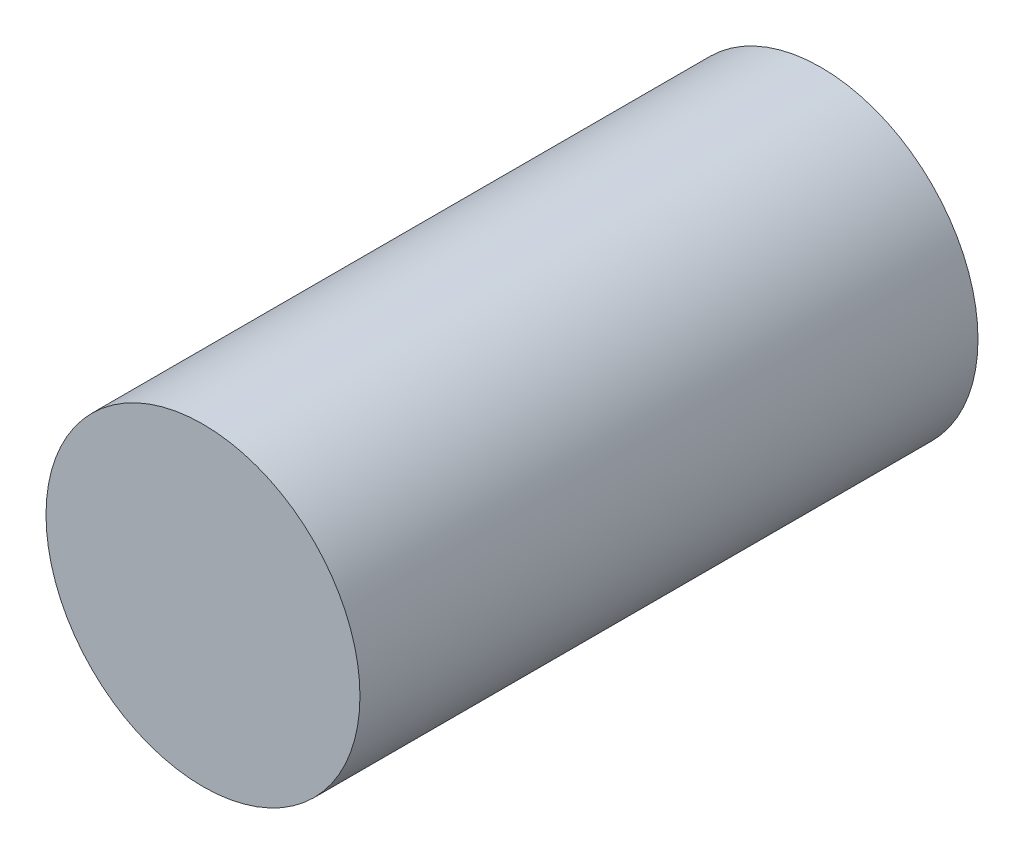
SolidWorks part; units mm, degrees
ref_plane "Front Plane" through (0, 0, 0) normal (0, 0, 1) x (1, 0, 0)
ref_plane "Top Plane" through (0, 0, 0) normal (0, 1, 0) x (1, 0, 0)
ref_plane "Right Plane" through (0, 0, 0) normal (1, 0, 0) x (0, 0, -1)
sketch "Sketch1" plane through (0, 0, 0) normal (0, 0, 1) x (1, 0, 0)
  circle A0 centre (0, 0) radius 12.7
extrude "Boss-Extrude1" add sketch "Sketch1" along normal blind 50
